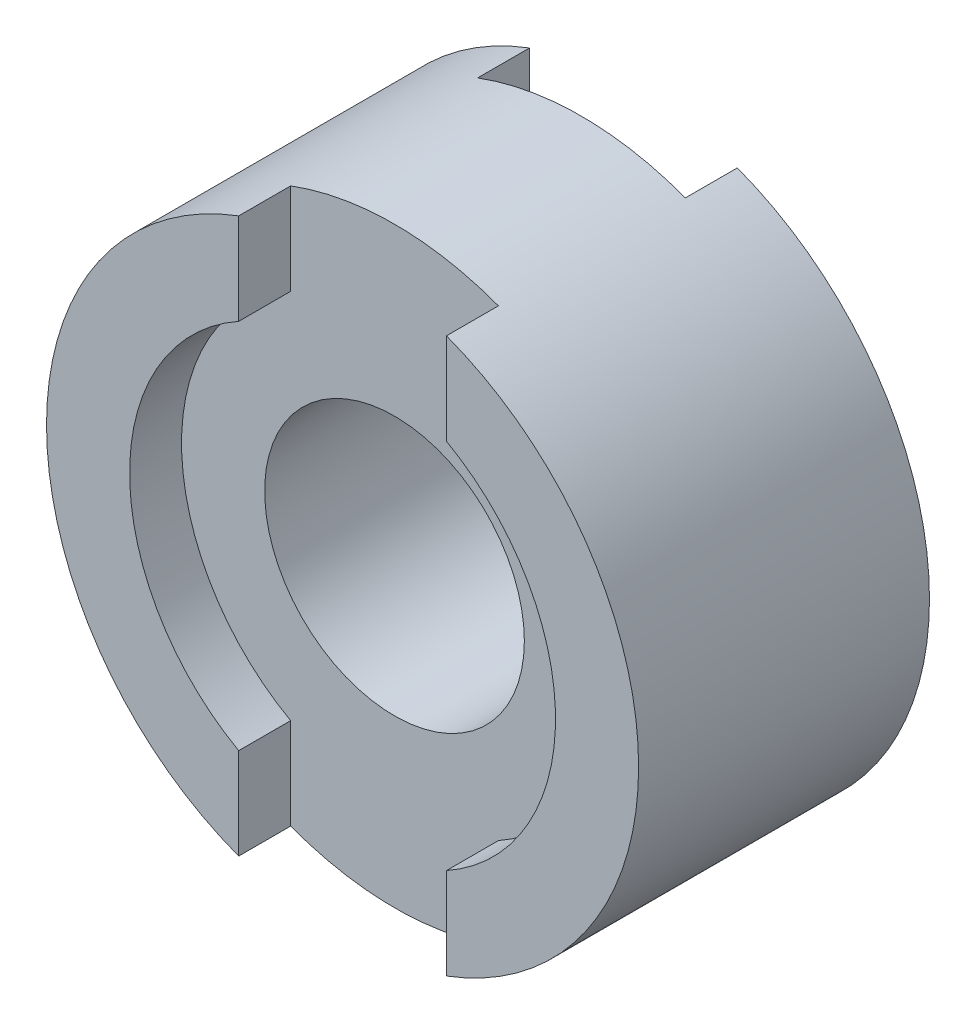
SolidWorks part; units mm, degrees
material "ABS"
ref_plane "正面" through (0, 0, 0) normal (0, 0, 1) x (1, 0, 0)
ref_plane "平面" through (0, 0, 0) normal (0, 1, 0) x (1, 0, 0)
ref_plane "右側面" through (0, 0, 0) normal (1, 0, 0) x (0, 0, -1)
sketch "ｽｹｯﾁ1" plane through (0, 0, 0) normal (0, 0, 1) x (1, 0, 0)
  circle A0 centre (0, 0) radius 2.85
  circle A1 centre (0, 0) radius 1.25
  dimension "D1" = 5.7
  dimension "D2" = 2.5
extrude "ﾎﾞｽ - 押し出し1" add sketch "ｽｹｯﾁ1" along normal blind 0.9
sketch "ｽｹｯﾁ2" plane through (0, 0, 0.9) normal (0, 0, 1) x (1, 0, 0)
  line L0 (0, 2.85) -> (0, -2.85) construction
  line L1 (-1, 2.6688) -> (-1, 1.7896)
  line L2 (-1, -1.7896) -> (-1, -2.6688)
  line L3 (1, 2.6688) -> (1, 1.7896)
  line L4 (1, -1.7896) -> (1, -2.6688)
  arc A0 (-1, 2.6688) -> (-1, -2.6688) centre (0, 0) ccw
  arc A1 (-1, 1.7896) -> (-1, -1.7896) centre (0, 0) ccw
  arc A2 (1, -1.7896) -> (1, 1.7896) centre (0, 0) ccw
  arc A3 (1, -2.6688) -> (1, 2.6688) centre (0, 0) ccw
  dimension "D1" = 4.1
  dimension "D2" = 5.7
  dimension "D3" = 1
  dimension "D4" = 1
extrude "ﾎﾞｽ - 押し出し2" add sketch "ｽｹｯﾁ2" along normal blind 0.5
mirror "ﾐﾗｰ1" about plane through (0, 0, 0) normal (0, 0, 1) of "ﾎﾞｽ - 押し出し2", "ﾎﾞｽ - 押し出し1"
